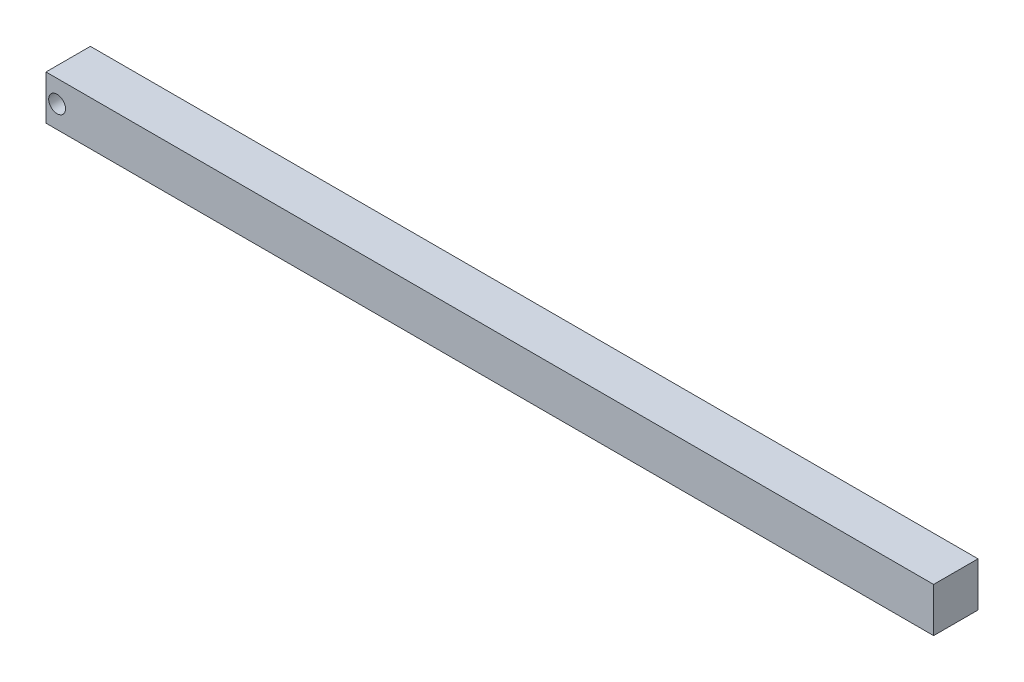
SolidWorks part; units mm, degrees
material "Plain Carbon Steel"
ref_plane "Front Plane" through (0, 0, 0) normal (0, 0, 1) x (1, 0, 0)
ref_plane "Top Plane" through (0, 0, 0) normal (0, 1, 0) x (1, 0, 0)
ref_plane "Right Plane" through (0, 0, 0) normal (1, 0, 0) x (0, 0, -1)
sketch "Sketch1" plane through (0, 0, 0) normal (0, 0, 1) x (1, 0, 0)
  line L0 (-100, -5) -> (100, -5)
  line L1 (100, -5) -> (100, 5)
  line L2 (100, 5) -> (-100, 5)
  line L3 (-100, 5) -> (-100, -5)
  dimension "D1" = 200
  dimension "D2" = 10
  dimension "D3" = 100
  dimension "D4" = 5
extrude "Boss-Extrude1" add sketch "Sketch1" along normal mid plane 10
sketch "Sketch2" plane through (0, 0, 0) normal (0, 0, 1) x (1, 0, 0)
  circle A0 centre (-97.5, 0) radius 1.9
  dimension "D2" = 3.8
  dimension "D1" = 97.5
extrude "Cut-Extrude1" cut sketch "Sketch2" against normal mid plane 30
